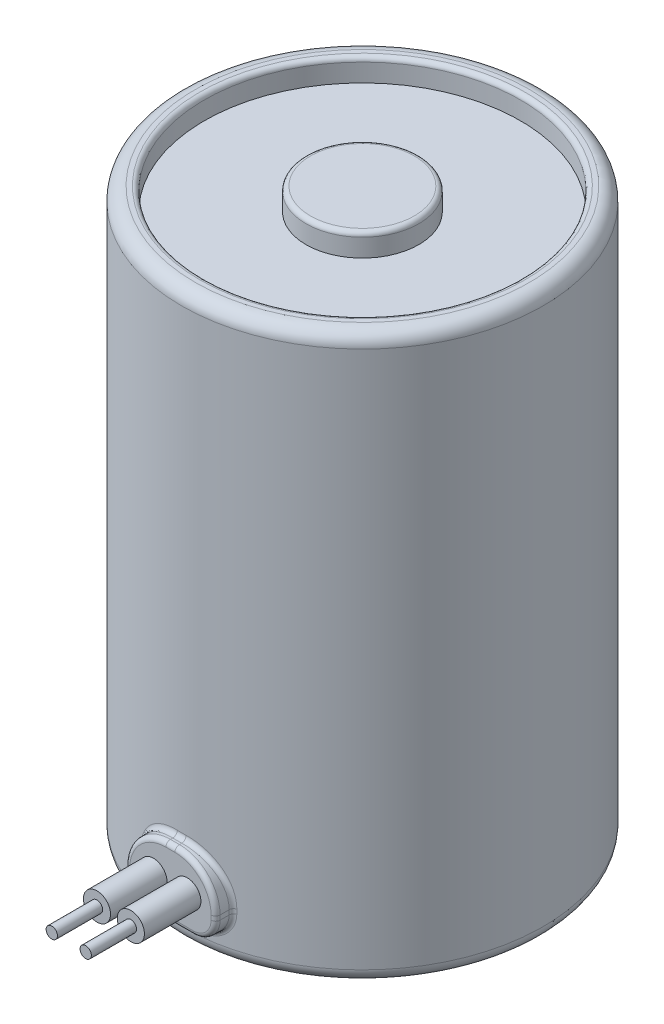
SolidWorks part; units mm, degrees
ref_plane "Front" through (0, 0, 0) normal (0, 0, 1) x (1, 0, 0)
ref_plane "Top" through (0, 0, 0) normal (0, 1, 0) x (1, 0, 0)
ref_plane "Right" through (0, 0, 0) normal (1, 0, 0) x (0, 0, -1)
sketch "Sketch11" plane through (0, 0, 0) normal (0, 1, 0) x (1, 0, 0)
  circle A0 centre (0, 0) radius 8 construction
  circle A1 centre (0, 0) radius 10 construction
  circle A2 centre (0, 0) radius 12.5 construction
  circle A3 centre (0, 0) radius 15 construction
  circle A4 centre (0, 0) radius 17 construction
  dimension "D1" = 16
  dimension "D2" = 20
  dimension "D3" = 25
  dimension "D4" = 30
  dimension "D5" = 34
sketch "Sketch1" plane through (0, 0, 0) normal (0, 1, 0) x (1, 0, 0)
  circle A0 centre (0, 0) radius 8
  circle A3 centre (0, 0) radius 8 construction
  circle A4 centre (0, 0) radius 10 construction
  circle A5 centre (0, 0) radius 12.5 construction
  circle A6 centre (0, 0) radius 15 construction
  circle A7 centre (0, 0) radius 17 construction
extrude "Boss-Extrude1" add sketch "Sketch1" along normal blind 25
ref_plane "Plane1" through (0, 0, 8) normal (0, 0, 1) x (1, 0, 0)
sketch "Sketch12" plane through (0, 25, 0) normal (0, 1, 0) x (1, 0, 0)
  circle A0 centre (0, 0) radius 2.5 construction
  circle A1 centre (0, 0) radius 4 construction
  circle A2 centre (0, 0) radius 5 construction
  circle A3 centre (0, 0) radius 6 construction
  circle A4 centre (0, 0) radius 8 construction
  dimension "D1" = 5
  dimension "D2" = 8
  dimension "D3" = 10
  dimension "D4" = 12
  dimension "D5" = 16
sketch "Sketch13" plane through (0, 0, 0) normal (0, 1, 0) x (1, 0, 0)
  circle A0 centre (0, 0) radius 16 construction
  circle A1 centre (0, 0) radius 14 construction
  circle A2 centre (0, 0) radius 11.5 construction
  circle A3 centre (0, 0) radius 9 construction
  circle A4 centre (0, 0) radius 7 construction
  dimension "D1" = 32
  dimension "D2" = 28
  dimension "D3" = 23
  dimension "D4" = 18
  dimension "D5" = 14
sketch "Sketch2" plane through (0, 25, 0) normal (0, 1, 0) x (1, 0, 0)
  circle A0 centre (0, 0) radius 7
  circle A1 centre (0, 0) radius 2.5
  circle A2 centre (0, 0) radius 2.5 construction
  circle A3 centre (0, 0) radius 4 construction
  circle A4 centre (0, 0) radius 5 construction
  circle A5 centre (0, 0) radius 6 construction
  circle A6 centre (0, 0) radius 8 construction
  circle A11 centre (0, 0) radius 16 construction
  circle A12 centre (0, 0) radius 14 construction
  circle A13 centre (0, 0) radius 11.5 construction
  circle A14 centre (0, 0) radius 9 construction
  circle A15 centre (0, 0) radius 7 construction
extrude "Cut-Extrude1" cut sketch "Sketch2" against normal blind 1
hole_wizard "M4 Tapped Hole1" positions "Sketch5" profile "Sketch7" tap size "M4" standard "ISO"
sketch "Sketch5" plane through (0, 0, 0) normal (0, -1, 0) x (-1, 0, 0)
  point P0 (0, 0)
sketch "Sketch7" plane through (0, 0, 0) normal (1, 0, 0) x (0, 0, -1)
  line L0 (0, 0) -> (0, 6.9526)
  line L1 (0, 6.9526) -> (1.65, 6)
  line L2 (1.65, 6) -> (1.65, 0.6)
  line L3 (1.65, 0.6) -> (2.25, 0)
  line L5 (2.25, 0) -> (0, 0)
  line L6 (-1.65, 0.6) -> (-2.25, 0) construction
  line L10 (0, 6.9526) -> (-1.65, 6) construction
  line L11 (0, -6.35) -> (0, 107.95) construction
  dimension "Tap Drill Dia." = 3.3
  dimension "Tap Drill Depth" = 6
  dimension "Near C'Sink Dia." = 4.5
  dimension "Near C'Sink Angle" = 90
  dimension "Drill Angle" = 120
cosmetic thread "Hole Thread1" parameters "D1"=6, "D2"=4
sketch "Sketch8" plane through (0, 0, 8) normal (0, 0, 1) x (1, 0, 0)
  line L0 (0, 0) -> (0, 25) construction
  line L1 (8, 25) -> (-8, 25) construction
  line L3 (-0.2, 4) -> (0.2, 4)
  line L4 (-2, 2.2) -> (-2, 2)
  line L5 (-1, 1) -> (1, 1)
  line L6 (2, 2.2) -> (2, 2)
  line L7 (-2, 4) -> (2, 1) construction
  line L8 (-2, 1) -> (2, 4) construction
  arc A0 (1, 1) -> (2, 2) centre (1, 2) ccw
  arc A1 (-2, 2) -> (-1, 1) centre (-1, 2) ccw
  arc A2 (0.2, 4) -> (2, 2.2) centre (0.2, 2.2) cw
  arc A3 (-0.2, 4) -> (-2, 2.2) centre (-0.2, 2.2) ccw
  point P6 (0, 2.5)
  dimension "D4" = 1.8
  dimension "D5" = 1
  dimension "D6" = 1.8
  dimension "D1" = 3
  dimension "D2" = 4
  dimension "D3" = 1
extrude "Boss-Extrude2" add sketch "Sketch8" along normal blind 0.5 and the other way up to surface other way up to face at (0, 25, 8)
sketch "Sketch9" plane through (0, 0, 8) normal (0, 0, 1) x (1, 0, 0)
  line L0 (0, 4) -> (0, 1) construction
  line L1 (0.2, 4) -> (-0.2, 4) construction
  line L2 (-1, 1) -> (1, 1) construction
  line L3 (-1.9748, 2.5) -> (1.9748, 2.5) construction
  arc A0 (-0.2, 4) -> (-2, 2.2) centre (-0.2, 2.2) ccw construction
  arc A1 (2, 2.2) -> (0.2, 4) centre (0.2, 2.2) ccw construction
  circle A2 centre (-0.75, 2.5) radius 0.6
  circle A3 centre (0.75, 2.5) radius 0.6
  dimension "D1" = 1.2
  dimension "D2" = 1.5
extrude "Boss-Extrude3" add sketch "Sketch9" along normal blind 3
sketch "Sketch10" plane through (0, 0, 8) normal (0, 0, 1) x (1, 0, 0)
  line L0 (0, 4) -> (0, 1) construction
  line L1 (0.2, 4) -> (-0.2, 4) construction
  line L2 (-1, 1) -> (1, 1) construction
  circle A0 centre (-0.75, 2.5) radius 0.25
  circle A1 centre (0.75, 2.5) radius 0.25
  dimension "D1" = 0.5
extrude "Boss-Extrude4" add sketch "Sketch10" along normal blind 5
fillet "Fillet1" radius 0.6 2 edges at (0, 0, 8) (0, 25, 8)
fillet "Fillet2" radius 0.2 16 edges at (0, 4, 8) (1.622, 3.3036, 7.8338) (2, 2.1, 7.746) (1.6285, 1.2222, 7.8325) (0, 1, 8) (-1.7911, 1.3883, 7.7969) (-2, 2.1, 7.746) (0, 4, 8.5) (1.4728, 3.4728, 8.5) (2, 2.1, 8.5) (1.7071, 1.2929, 8.5) (0, 1, 8.5) (-1.7071, 1.2929, 8.5) (-2, 2.1, 8.5) (-1.3105, 3.6166, 7.8919) (-1.4728, 3.4728, 8.5)
fillet "Fillet3" radius 0.2 1 edges at (0, 25, 2.5)
fillet "Fillet4" radius 0.2 1 edges at (0, 25, 7)
